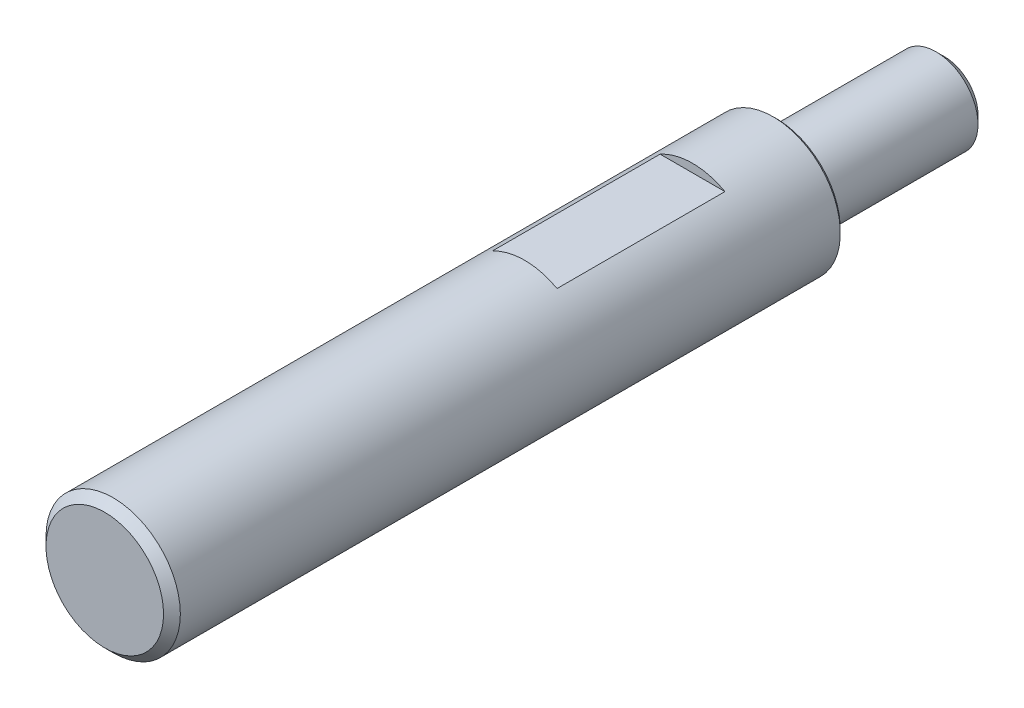
SolidWorks part; units mm, degrees
material "45#鋼"
ref_plane "前基準面" through (0, 0, 0) normal (0, 0, 1) x (1, 0, 0)
ref_plane "上基準面" through (0, 0, 0) normal (0, 1, 0) x (1, 0, 0)
ref_plane "右基準面" through (0, 0, 0) normal (1, 0, 0) x (0, 0, -1)
sketch "草圖1" plane through (0, 0, 0) normal (0, 0, 1) x (1, 0, 0)
  circle A0 centre (0, 0) radius 4
  dimension "D1" = 8
extrude "填料-伸長1" add sketch "草圖1" along normal mid plane 50
sketch "草圖2" plane through (0, 0, -25) normal (0, 0, -1) x (-1, 0, 0)
  circle A0 centre (0, 0) radius 4
  circle A1 centre (0, 0) radius 2.5
  dimension "D1" = 5
extrude "除料-伸長1" cut sketch "草圖2" against normal blind 10
cosmetic thread "裝飾螺紋線1" parameters "D1"=10, "D2"=4.134
chamfer "導角1" distance 0.5 angle 45 1 edges at (-2.5, 0, -25)
chamfer "導角2" distance 0.2 angle 45 1 edges at (-4, 0, -15)
sketch "草圖3" plane through (0, 0, 0) normal (1, 0, 0) x (0, 0, -1)
  line L1 (0, 4.0056) -> (10, 4.0056)
  line L2 (0, 4.0056) -> (0, 3.5028)
  line L3 (0, 3.5028) -> (10, 3.5028)
  line L4 (10, 4.0056) -> (10, 3.5028)
  line L6 (0, -4) -> (10, -4)
  line L7 (0, -4) -> (0, -3.4972)
  line L8 (0, -3.4972) -> (10, -3.4972)
  line L9 (10, -4) -> (10, -3.4972)
  line L11 (-25, -4) -> (14.8, -4) construction
  line L12 (15, -3.8) -> (15, 3.8) construction
  dimension "D1" = 7
  dimension "D2" = 5
  dimension "D3" = 10
extrude "除料-伸長2" cut sketch "草圖3" against normal mid plane 10
chamfer "導角3" distance 0.5 angle 45 1 edges at (4, 0, 25)
